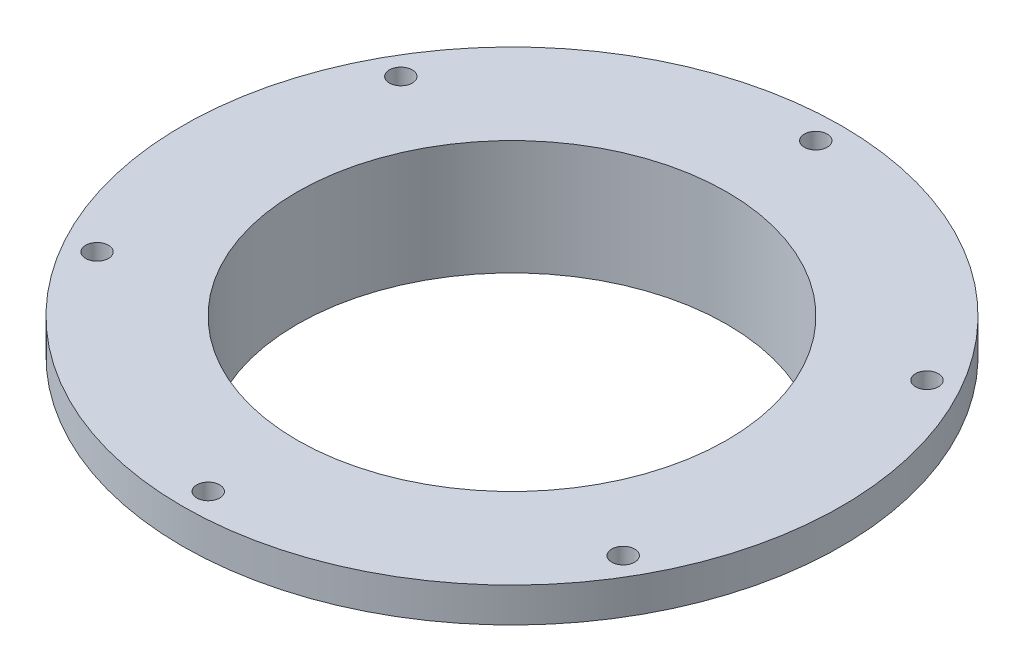
SolidWorks part; units mm, degrees
material "PBT General Purpose"
ref_plane "Front Plane" through (0, 0, 0) normal (0, 0, 1) x (1, 0, 0)
ref_plane "Top Plane" through (0, 0, 0) normal (0, 1, 0) x (1, 0, 0)
ref_plane "Right Plane" through (0, 0, 0) normal (1, 0, 0) x (0, 0, -1)
sketch "Sketch1" plane through (0, 0, 0) normal (1, 0, 0) x (0, 0, -1)
  line L0 (37.5, 66.4015) -> (57.5, 80.3684)
  line L5 (57.5, 80.3684) -> (57.5, 86.4015)
  line L6 (57.5, 86.4015) -> (37.5, 86.4015)
  line L7 (37.5, 86.4015) -> (37.5, 66.4015)
  line L8 (0, 0) -> (0, 88.6674) construction
  line L9 (31.6948, 62.3474) -> (58.0521, 80.754) construction
  dimension "D1" = 57.5
  dimension "D2" = 20
  dimension "D4" = 20
revolve "Revolve1" add sketch "Sketch1" angle 360 about L8
sketch "Sketch2" plane through (0, 86.4015, 0) normal (0, 1, 0) x (1, 0, 0)
  line L0 (0, -37.5) -> (0, -57.5) construction
  circle A0 centre (0, -53) radius 2
  circle A1 centre (0, 0) radius 37.5 construction
  circle A2 centre (0, 0) radius 57.5 construction
  circle A3 centre (-45.8993, -26.5) radius 2
  circle A4 centre (-45.8993, 26.5) radius 2
  circle A5 centre (0, 53) radius 2
  circle A6 centre (45.8993, 26.5) radius 2
  circle A7 centre (45.8993, -26.5) radius 2
  point P22 (0, 0)
  dimension "D2" = 4
  dimension "D3" = 53
  dimension "D1" = 6
extrude "Cut-Extrude1" cut sketch "Sketch2" against normal through all
sketch3d "3DSketch3"
  point P0 (-67.5, 53.9015, -67.5)
